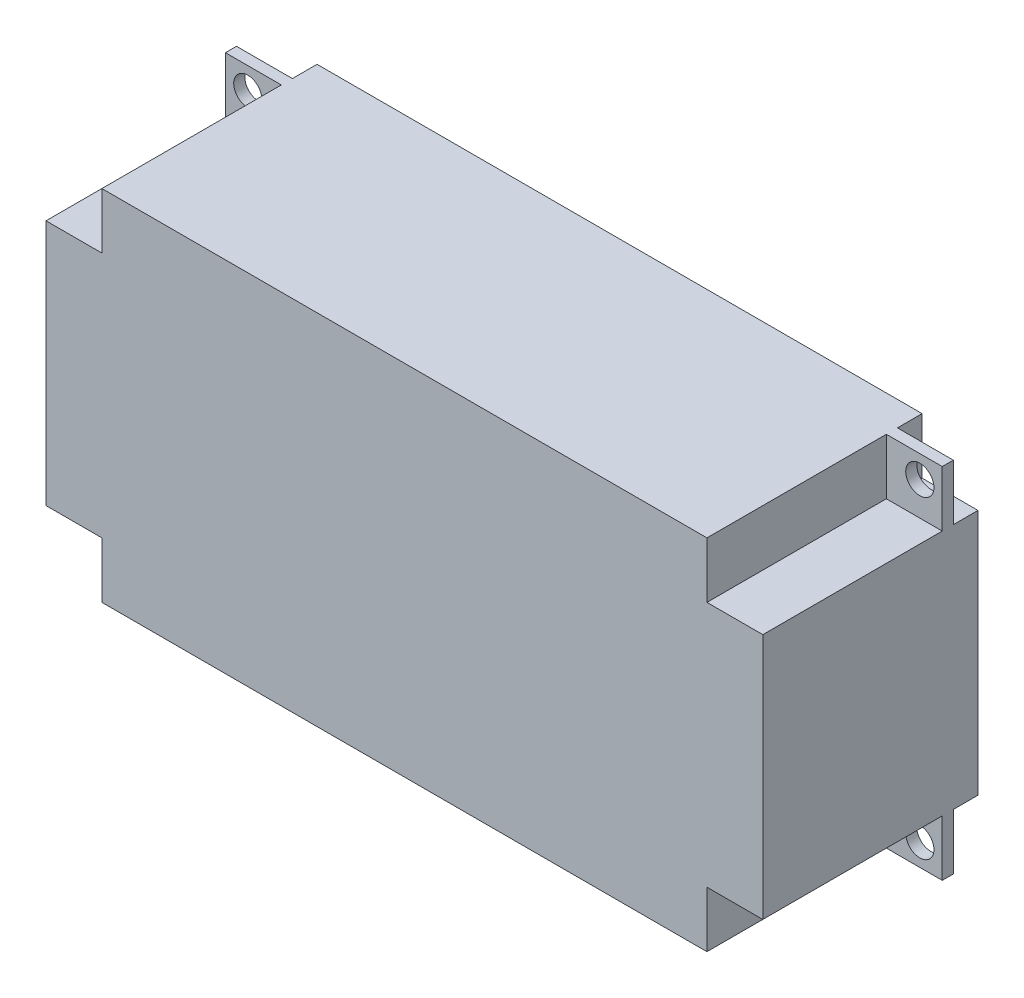
SolidWorks part; units mm, degrees
ref_plane "Piano frontale" through (0, 0, 0) normal (0, 0, 1) x (1, 0, 0)
ref_plane "Piano superiore" through (0, 0, 0) normal (0, 1, 0) x (1, 0, 0)
ref_plane "Piano destro" through (0, 0, 0) normal (1, 0, 0) x (0, 0, -1)
sketch "Schizzo1" plane through (0, 0, 0) normal (0, 0, 1) x (1, 0, 0)
  line L1 (-50.8, -25.4) -> (50.8, -25.4)
  line L2 (-50.8, -25.4) -> (-50.8, 25.4)
  line L3 (-50.8, 25.4) -> (50.8, 25.4)
  line L4 (50.8, -25.4) -> (50.8, 25.4)
  line L5 (-50.8, -25.4) -> (50.8, 25.4) construction
  line L6 (-50.8, 25.4) -> (50.8, -25.4) construction
  point P1 (0, 0)
  dimension "D1" = 101.6
  dimension "D2" = 50.8
extrude "Estrusione-Estrusione1" add sketch "Schizzo1" along normal blind 1.57
sketch "Schizzo2" plane through (0, 0, 1.57) normal (0, 0, 1) x (1, 0, 0)
  line L0 (50.8, 25.4) -> (-50.8, 25.4) construction
  line L1 (-50.8, 25.4) -> (-50.8, -25.4) construction
  circle A0 centre (-47.625, 22.225) radius 2
  circle A1 centre (47.625, 22.225) radius 2
  circle A2 centre (47.625, -22.225) radius 2
  circle A3 centre (-47.625, -22.225) radius 2
  dimension "D1" = 4
  dimension "D2" = 3.175
  dimension "D3" = 3.175
  dimension "D6" = 95.25
  dimension "D7" = 44.45
  dimension "D4" = 2
  dimension "D5" = 2
extrude "Taglio-Estrusione1" cut sketch "Schizzo2" against normal through all
sketch "Schizzo3" plane through (0, 0, 1.57) normal (0, 0, 1) x (1, 0, 0)
  line L0 (-50.8, 17.48) -> (-42.88, 17.48)
  line L1 (-50.8, 25.4) -> (-50.8, -25.4) construction
  line L2 (-42.88, 17.48) -> (-42.88, 25.4)
  line L3 (50.8, 25.4) -> (-50.8, 25.4) construction
  line L4 (-42.88, 25.4) -> (42.88, 25.4)
  line L5 (42.88, 25.4) -> (42.88, 17.48)
  line L6 (42.88, 17.48) -> (50.8, 17.48)
  line L7 (50.8, -25.4) -> (50.8, 25.4) construction
  line L8 (50.8, 17.48) -> (50.8, -17.48)
  line L9 (50.8, -17.48) -> (42.88, -17.48)
  line L10 (42.88, -17.48) -> (42.88, -25.4)
  line L11 (-50.8, -25.4) -> (50.8, -25.4) construction
  line L12 (42.88, -25.4) -> (-42.88, -25.4)
  line L13 (-42.88, -25.4) -> (-42.88, -17.48)
  line L14 (-42.88, -17.48) -> (-50.8, -17.48)
  line L15 (-50.8, -17.48) -> (-50.8, 17.48)
  dimension "D1" = 7.92
extrude "Estrusione-Estrusione2" add sketch "Schizzo3" against normal blind 5.07 and the other way blind 25.43
